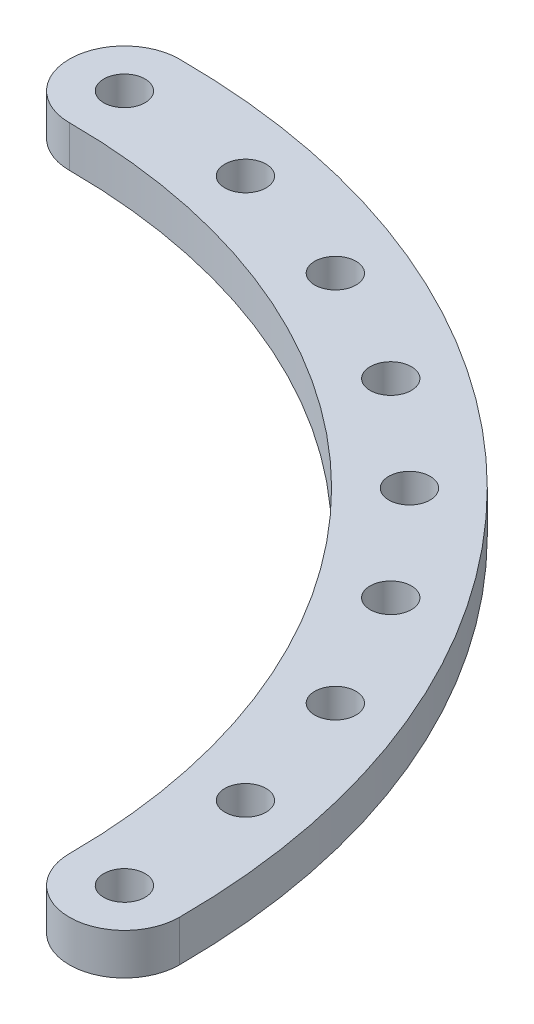
SolidWorks part; units mm, degrees
ref_plane "Front Plane" through (0, 0, 0) normal (0, 0, 1) x (1, 0, 0)
ref_plane "Top Plane" through (0, 0, 0) normal (0, 1, 0) x (1, 0, 0)
ref_plane "Right Plane" through (0, 0, 0) normal (1, 0, 0) x (0, 0, -1)
sketch "Sketch1" plane through (0, 0, 0) normal (0, 1, 0) x (1, 0, 0)
  line L0 (0, 0) -> (-5.2929, 53.74)
  line L1 (0, 0) -> (53.74, -5.2929)
  line L2 (0, 46) -> (0, 0)
  circle A0 centre (0, 0) radius 46
  circle A1 centre (0, 0) radius 54
  circle A2 centre (0, 50) radius 1.5
  circle A3 centre (9.7545, 49.0393) radius 1.5
  circle A4 centre (19.1342, 46.194) radius 1.5
  circle A5 centre (27.7785, 41.5735) radius 1.5
  circle A6 centre (35.3553, 35.3553) radius 1.5
  circle A7 centre (41.5735, 27.7785) radius 1.5
  circle A8 centre (46.194, 19.1342) radius 1.5
  circle A9 centre (49.0393, 9.7545) radius 1.5
  circle A10 centre (50, 0) radius 1.5
  circle A11 centre (49.0393, -9.7545) radius 1.5
  circle A12 centre (46.194, -19.1342) radius 1.5
  circle A13 centre (41.5735, -27.7785) radius 1.5
  circle A14 centre (35.3553, -35.3553) radius 1.5
  circle A15 centre (27.7785, -41.5735) radius 1.5
  circle A16 centre (19.1342, -46.194) radius 1.5
  circle A17 centre (9.7545, -49.0393) radius 1.5
  circle A18 centre (0, -50) radius 1.5
  circle A19 centre (-9.7545, -49.0393) radius 1.5
  circle A20 centre (-19.1342, -46.194) radius 1.5
  circle A21 centre (-27.7785, -41.5735) radius 1.5
  circle A22 centre (-35.3553, -35.3553) radius 1.5
  circle A23 centre (-41.5735, -27.7785) radius 1.5
  circle A24 centre (-46.194, -19.1342) radius 1.5
  circle A25 centre (-49.0393, -9.7545) radius 1.5
  circle A26 centre (-50, 0) radius 1.5
  circle A27 centre (-49.0393, 9.7545) radius 1.5
  circle A28 centre (-46.194, 19.1342) radius 1.5
  circle A29 centre (-41.5735, 27.7785) radius 1.5
  circle A30 centre (-35.3553, 35.3553) radius 1.5
  circle A31 centre (-27.7785, 41.5735) radius 1.5
  circle A32 centre (-19.1342, 46.194) radius 1.5
  circle A33 centre (-9.7545, 49.0393) radius 1.5
  point P71 (0, 0)
  dimension "D1" = 92
  dimension "D4" = 3
  dimension "D5" = 32
  dimension "D3" = 50
  dimension "D6" = 5.625
  dimension "D7" = 95.625
  dimension "D2" = 8
extrude "Boss-Extrude1" add sketch "Sketch1" along normal blind 3 contours L1 A1 L0 A0 A10 A9 A8 A7 A6 A5 A4 A3 A2
sketch "Sketch2" plane through (0, 3, 0) normal (0, 1, 0) x (1, 0, 0)
  circle A0 centre (0, 50) radius 4
  circle A1 centre (50, 0) radius 4
  circle A2 centre (0, 0) radius 54
  circle A3 centre (0, 0) radius 71
  line M10 (45.7785, -4.5088) -> (53.74, -5.2929)
  arc M11 (53.74, -5.2929) -> (-5.2929, 53.74) centre (0, 0) ccw
  line M12 (-5.2929, 53.74) -> (-4.5088, 45.7785)
  arc M13 (-4.5088, 45.7785) -> (45.7785, -4.5088) centre (0, 0) cw
extrude "Cut-Extrude1" cut sketch "Sketch2" against normal blind 3 contours A0 M11 M12 M13 | A1 M13 M10 M11
